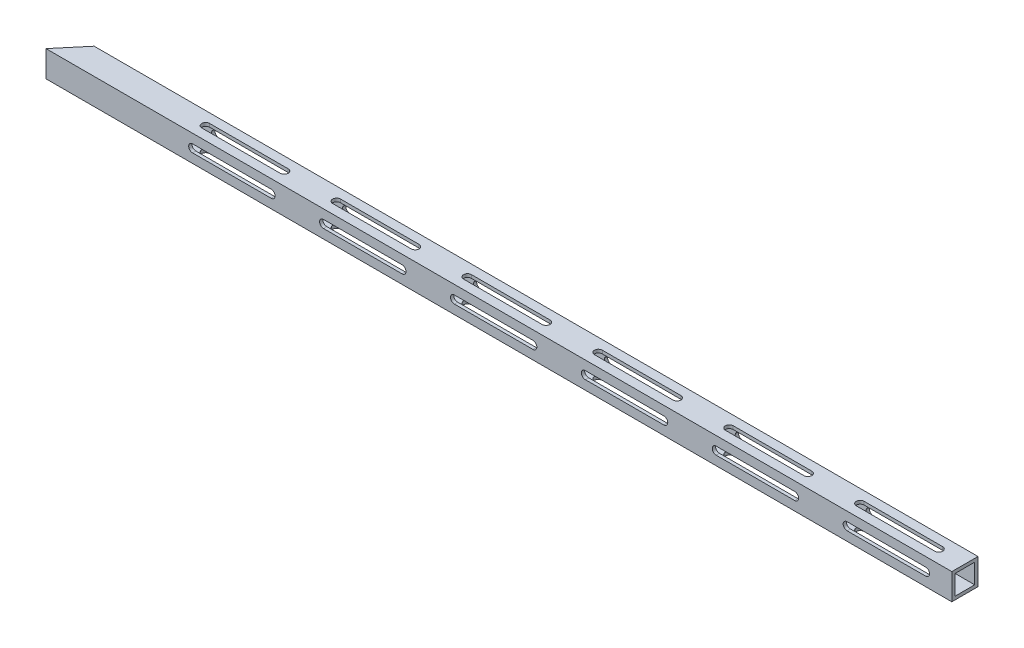
SolidWorks part; units mm, degrees
material "Plain Carbon Steel"
ref_plane "Front Plane" through (0, 0, 0) normal (0, 0, 1) x (1, 0, 0)
ref_plane "Top Plane" through (0, 0, 0) normal (0, 1, 0) x (1, 0, 0)
ref_plane "Right Plane" through (0, 0, 0) normal (1, 0, 0) x (0, 0, -1)
sketch "Sketch1" plane through (0, 0, 0) normal (1, 0, 0) x (0, 0, -1)
  line L0 (4.7625, 4.7625) -> (-4.7625, 4.7625)
  line L1 (6.35, 6.35) -> (-6.35, 6.35)
  line L2 (6.35, 6.35) -> (6.35, -6.35)
  line L3 (6.35, -6.35) -> (-6.35, -6.35)
  line L4 (-6.35, 6.35) -> (-6.35, -6.35)
  line L5 (6.35, 6.35) -> (-6.35, -6.35) construction
  line L6 (6.35, -6.35) -> (-6.35, 6.35) construction
  line L7 (-4.7625, 4.7625) -> (-4.7625, -4.7625)
  line L8 (4.7625, -4.7625) -> (-4.7625, -4.7625)
  line L9 (4.7625, 4.7625) -> (4.7625, -4.7625)
  dimension "D1" = 12.7
  dimension "D2" = 12.7
  dimension "D3" = 1.5875
extrude "Boss-Extrude1" add sketch "Sketch1" against normal blind 185.42 and the other way blind 254
sketch "Sketch2" plane through (0, 0, 0) normal (0, 1, 0) x (1, 0, 0)
  line L0 (-185.42, -6.35) -> (-135.9836, 52.566) construction
  line L1 (-185.42, -6.35) -> (-174.2505, 6.9613)
  line L2 (-185.42, -6.35) -> (-194.2478, 1.0574)
  line L3 (-174.2505, 6.9613) -> (-183.0782, 14.3687)
  line L4 (-194.2478, 1.0574) -> (-183.0782, 14.3687)
extrude "Cut-Extrude1" cut sketch "Sketch2" against normal through all and the other way through all
sketch "Sketch3" plane through (0, 6.35, 0) normal (0, 1, 0) x (1, 0, 0)
  line L0 (-114.3, 0) -> (-76.2, 0) construction
  line L1 (-114.3, 1.905) -> (-76.2, 1.905)
  line L2 (-114.3, -1.905) -> (-76.2, -1.905)
  line L3 (-50.8, 0) -> (-12.7, 0) construction
  line L6 (-50.8, 1.905) -> (-12.7, 1.905)
  line L9 (-50.8, -1.905) -> (-12.7, -1.905)
  line L10 (12.7, 0) -> (50.8, 0) construction
  line L11 (12.7, 1.905) -> (50.8, 1.905)
  line L12 (12.7, -1.905) -> (50.8, -1.905)
  line L13 (76.2, 0) -> (114.3, 0) construction
  line L14 (76.2, 1.905) -> (114.3, 1.905)
  line L15 (76.2, -1.905) -> (114.3, -1.905)
  line L16 (139.7, 0) -> (177.8, 0) construction
  line L17 (139.7, 1.905) -> (177.8, 1.905)
  line L18 (139.7, -1.905) -> (177.8, -1.905)
  line L19 (203.2, 0) -> (241.3, 0) construction
  line L20 (203.2, 1.905) -> (241.3, 1.905)
  line L21 (203.2, -1.905) -> (241.3, -1.905)
  line L22 (254, 6.35) -> (254, -6.35) construction
  arc A0 (-114.3, 1.905) -> (-114.3, -1.905) centre (-114.3, 0) ccw
  arc A1 (-76.2, -1.905) -> (-76.2, 1.905) centre (-76.2, 0) ccw
  arc A2 (-50.8, 1.905) -> (-50.8, -1.905) centre (-50.8, 0) ccw
  arc A3 (-12.7, -1.905) -> (-12.7, 1.905) centre (-12.7, 0) ccw
  arc A4 (12.7, 1.905) -> (12.7, -1.905) centre (12.7, 0) ccw
  arc A5 (50.8, -1.905) -> (50.8, 1.905) centre (50.8, 0) ccw
  arc A6 (76.2, 1.905) -> (76.2, -1.905) centre (76.2, 0) ccw
  arc A7 (114.3, -1.905) -> (114.3, 1.905) centre (114.3, 0) ccw
  arc A8 (139.7, 1.905) -> (139.7, -1.905) centre (139.7, 0) ccw
  arc A9 (177.8, -1.905) -> (177.8, 1.905) centre (177.8, 0) ccw
  arc A10 (203.2, 1.905) -> (203.2, -1.905) centre (203.2, 0) ccw
  arc A11 (241.3, -1.905) -> (241.3, 1.905) centre (241.3, 0) ccw
  point P3 (-95.25, 0)
  point P10 (-31.75, 0)
  point P17 (31.75, 0)
  point P24 (95.25, 0)
  point P31 (158.75, 0)
  point P38 (222.25, 0)
  dimension "D1" = 38.1
  dimension "D2" = 3.81
  dimension "D3" = 38.1
  dimension "D4" = 3.81
  dimension "D5" = 38.1
  dimension "D6" = 3.81
  dimension "D7" = 25.4
  dimension "D8" = 25.4
  dimension "D9" = 38.1
  dimension "D10" = 3.81
  dimension "D11" = 38.1
  dimension "D12" = 3.81
  dimension "D13" = 38.1
  dimension "D14" = 3.81
  dimension "D15" = 25.4
  dimension "D16" = 25.4
  dimension "D17" = 25.4
  dimension "D18" = 12.7
extrude "Cut-Extrude2" cut sketch "Sketch3" against normal through all
sketch "Sketch4" plane through (0, 0, 6.35) normal (0, 0, 1) x (1, 0, 0)
  line L0 (-114.3, 0) -> (-76.2, 0) construction
  line L1 (-114.3, 1.905) -> (-76.2, 1.905)
  line L2 (-114.3, -1.905) -> (-76.2, -1.905)
  line L3 (-50.8, 0) -> (-12.7, 0) construction
  line L4 (-50.8, 1.905) -> (-12.7, 1.905)
  line L5 (-50.8, -1.905) -> (-12.7, -1.905)
  line L6 (12.7, 0) -> (50.8, 0) construction
  line L7 (12.7, 1.905) -> (50.8, 1.905)
  line L8 (12.7, -1.905) -> (50.8, -1.905)
  line L9 (76.2, 0) -> (114.3, 0) construction
  line L10 (76.2, 1.905) -> (114.3, 1.905)
  line L11 (76.2, -1.905) -> (114.3, -1.905)
  line L12 (139.7, 0) -> (177.8, 0) construction
  line L13 (139.7, 1.905) -> (177.8, 1.905)
  line L14 (139.7, -1.905) -> (177.8, -1.905)
  line L15 (203.2, 0) -> (241.3, 0) construction
  line L16 (203.2, 1.905) -> (241.3, 1.905)
  line L17 (203.2, -1.905) -> (241.3, -1.905)
  line L18 (254, 6.35) -> (254, -6.35) construction
  arc A0 (-114.3, 1.905) -> (-114.3, -1.905) centre (-114.3, 0) ccw
  arc A1 (-76.2, -1.905) -> (-76.2, 1.905) centre (-76.2, 0) ccw
  arc A2 (-50.8, 1.905) -> (-50.8, -1.905) centre (-50.8, 0) ccw
  arc A3 (-12.7, -1.905) -> (-12.7, 1.905) centre (-12.7, 0) ccw
  arc A4 (12.7, 1.905) -> (12.7, -1.905) centre (12.7, 0) ccw
  arc A5 (50.8, -1.905) -> (50.8, 1.905) centre (50.8, 0) ccw
  arc A6 (76.2, 1.905) -> (76.2, -1.905) centre (76.2, 0) ccw
  arc A7 (114.3, -1.905) -> (114.3, 1.905) centre (114.3, 0) ccw
  arc A8 (139.7, 1.905) -> (139.7, -1.905) centre (139.7, 0) ccw
  arc A9 (177.8, -1.905) -> (177.8, 1.905) centre (177.8, 0) ccw
  arc A10 (203.2, 1.905) -> (203.2, -1.905) centre (203.2, 0) ccw
  arc A11 (241.3, -1.905) -> (241.3, 1.905) centre (241.3, 0) ccw
  point P3 (-95.25, 0)
  point P8 (-31.75, 0)
  point P15 (31.75, 0)
  point P22 (95.25, 0)
  point P29 (158.75, 0)
  point P36 (222.25, 0)
  point P43 (254, 0)
  dimension "D1" = 38.1
  dimension "D2" = 3.81
  dimension "D3" = 12.7
  dimension "D4" = 25.4
  dimension "D5" = 25.4
  dimension "D6" = 25.4
  dimension "D7" = 25.4
  dimension "D8" = 25.4
extrude "Cut-Extrude3" cut sketch "Sketch4" against normal through all
